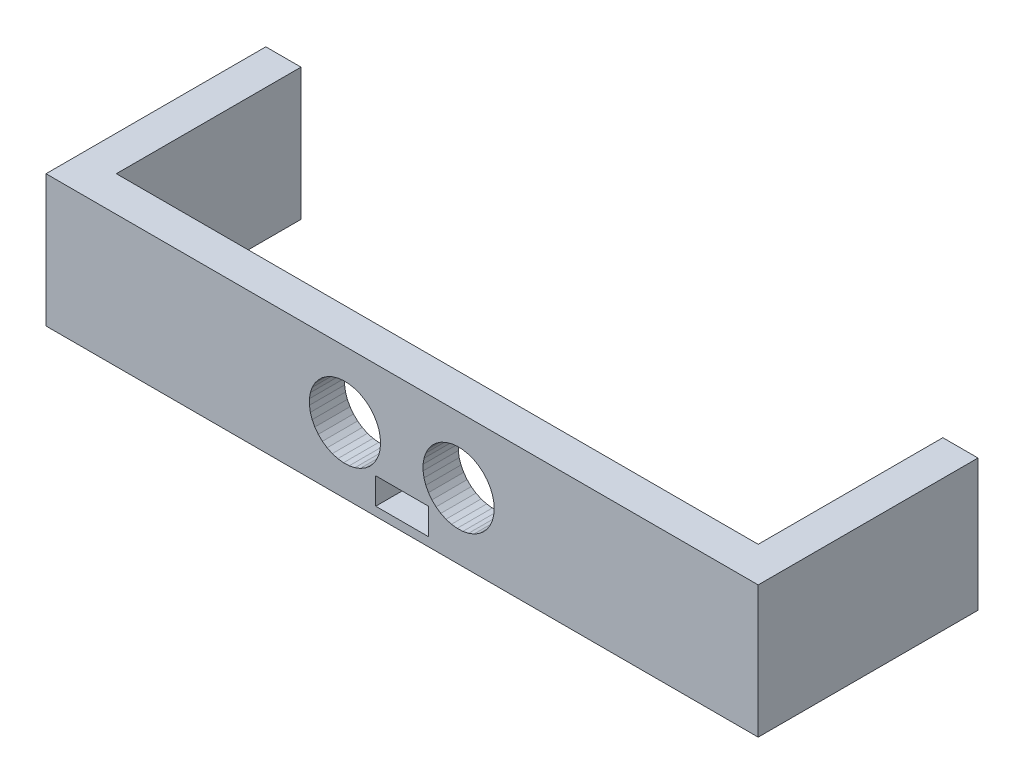
SolidWorks part; units mm, degrees
ref_plane "Front Plane" through (0, 0, 0) normal (0, 0, 1) x (1, 0, 0)
ref_plane "Top Plane" through (0, 0, 0) normal (0, 1, 0) x (1, 0, 0)
ref_plane "Right Plane" through (0, 0, 0) normal (1, 0, 0) x (0, 0, -1)
ref_plane "Plane1" through (0, 30, 0) normal (0, 1, 0) x (1, 0, 0)
sketch "Sketch1" plane through (0, 30, 0) normal (0, 1, 0) x (1, 0, 0)
  line L0 (162, 0) -> (0, 0)
  line L1 (0, 0) -> (0, -50)
  line L2 (0, -50) -> (162, -50)
  line L3 (162, -50) -> (162, 0)
extrude "Boss-Extrude1" add sketch "Sketch1" against normal blind 30
sketch "Sketch2" plane through (0, 0, 0) normal (0, -1, 0) x (1, 0, 0)
  line L0 (8, 0) -> (154, 0)
  line L1 (154, 0) -> (154, 42)
  line L2 (154, 42) -> (8, 42)
  line L3 (8, 42) -> (8, 0)
extrude "Cut-Extrude1" cut sketch "Sketch2" against normal through all
sketch "Sketch3" plane through (0, 0, 50) normal (0, 0, 1) x (1, 0, 0)
  line L0 (85.7763, 14.3482) -> (85.9854, 13.0615)
  line L1 (85.9854, 13.0615) -> (86.3982, 11.8251)
  line L2 (86.3982, 11.8251) -> (87.004, 10.6708)
  line L3 (87.004, 10.6708) -> (87.7871, 9.6287)
  line L4 (87.7871, 9.6287) -> (88.7272, 8.7257)
  line L5 (88.7272, 8.7257) -> (89.8, 7.9852)
  line L6 (89.8, 7.9852) -> (90.9777, 7.4264)
  line L7 (90.9777, 7.4264) -> (92.2298, 7.0637)
  line L8 (92.2298, 7.0637) -> (93.5239, 6.9066)
  line L9 (93.5239, 6.9066) -> (94.8263, 6.9591)
  line L10 (94.8263, 6.9591) -> (96.1036, 7.2198)
  line L11 (96.1036, 7.2198) -> (97.3224, 7.6821)
  line L12 (97.3224, 7.6821) -> (98.4513, 8.3338)
  line L13 (98.4513, 8.3338) -> (99.4611, 9.1583)
  line L14 (99.4611, 9.1583) -> (100.3255, 10.134)
  line L15 (100.3255, 10.134) -> (101.0222, 11.2357)
  line L16 (101.0222, 11.2357) -> (101.5331, 12.435)
  line L17 (101.5331, 12.435) -> (101.8451, 13.7007)
  line L18 (101.8451, 13.7007) -> (101.95, 15)
  line L19 (101.95, 15) -> (101.8451, 16.2993)
  line L20 (101.8451, 16.2993) -> (101.5331, 17.565)
  line L21 (101.5331, 17.565) -> (101.0222, 18.7643)
  line L22 (101.0222, 18.7643) -> (100.3255, 19.866)
  line L23 (100.3255, 19.866) -> (99.4611, 20.8417)
  line L24 (99.4611, 20.8417) -> (98.4513, 21.6662)
  line L25 (98.4513, 21.6662) -> (97.3224, 22.3179)
  line L26 (97.3224, 22.3179) -> (96.1036, 22.7802)
  line L27 (96.1036, 22.7802) -> (94.8263, 23.0409)
  line L28 (94.8263, 23.0409) -> (93.5239, 23.0934)
  line L29 (93.5239, 23.0934) -> (92.2298, 22.9363)
  line L30 (92.2298, 22.9363) -> (90.9777, 22.5736)
  line L31 (90.9777, 22.5736) -> (89.8, 22.0148)
  line L32 (89.8, 22.0148) -> (88.7272, 21.2743)
  line L33 (88.7272, 21.2743) -> (87.7871, 20.3713)
  line L34 (87.7871, 20.3713) -> (87.004, 19.3292)
  line L35 (87.004, 19.3292) -> (86.3982, 18.1749)
  line L36 (86.3982, 18.1749) -> (85.9854, 16.9385)
  line L37 (85.9854, 16.9385) -> (85.7763, 15.6518)
  line L38 (85.7763, 15.6518) -> (85.7763, 14.3482)
extrude "Cut-Extrude2" cut sketch "Sketch3" against normal through all
sketch "Sketch4" plane through (0, 0, 50) normal (0, 0, 1) x (1, 0, 0)
  line L0 (87, 8) -> (75, 8)
  line L1 (75, 8) -> (75, 2)
  line L2 (75, 2) -> (87, 2)
  line L3 (87, 2) -> (87, 8)
extrude "Cut-Extrude3" cut sketch "Sketch4" against normal through all
sketch "Sketch5" plane through (0, 0, 42) normal (0, 0, -1) x (-1, 0, 0)
  line L0 (-70.2536, 22.7802) -> (-71.4724, 22.3179)
  line L1 (-71.4724, 22.3179) -> (-72.6013, 21.6662)
  line L2 (-72.6013, 21.6662) -> (-73.6111, 20.8417)
  line L3 (-73.6111, 20.8417) -> (-74.4755, 19.866)
  line L4 (-74.4755, 19.866) -> (-75.1722, 18.7643)
  line L5 (-75.1722, 18.7643) -> (-75.6831, 17.565)
  line L6 (-75.6831, 17.565) -> (-75.9951, 16.2993)
  line L7 (-75.9951, 16.2993) -> (-76.1, 15)
  line L8 (-76.1, 15) -> (-75.9951, 13.7007)
  line L9 (-75.9951, 13.7007) -> (-75.6831, 12.435)
  line L10 (-75.6831, 12.435) -> (-75.1722, 11.2357)
  line L11 (-75.1722, 11.2357) -> (-74.4755, 10.134)
  line L12 (-74.4755, 10.134) -> (-73.6111, 9.1583)
  line L13 (-73.6111, 9.1583) -> (-72.6013, 8.3338)
  line L14 (-72.6013, 8.3338) -> (-71.4724, 7.6821)
  line L15 (-71.4724, 7.6821) -> (-70.2536, 7.2198)
  line L16 (-70.2536, 7.2198) -> (-68.9764, 6.9591)
  line L17 (-68.9764, 6.9591) -> (-67.6738, 6.9066)
  line L18 (-67.6738, 6.9066) -> (-66.3798, 7.0637)
  line L19 (-66.3798, 7.0637) -> (-65.1277, 7.4264)
  line L20 (-65.1277, 7.4264) -> (-63.95, 7.9852)
  line L21 (-63.95, 7.9852) -> (-62.8772, 8.7257)
  line L22 (-62.8772, 8.7257) -> (-61.9371, 9.6287)
  line L23 (-61.9371, 9.6287) -> (-61.154, 10.6708)
  line L24 (-61.154, 10.6708) -> (-60.5482, 11.8251)
  line L25 (-60.5482, 11.8251) -> (-60.1354, 13.0615)
  line L26 (-60.1354, 13.0615) -> (-59.9263, 14.3482)
  line L27 (-59.9263, 14.3482) -> (-59.9263, 15.6518)
  line L28 (-59.9263, 15.6518) -> (-60.1354, 16.9385)
  line L29 (-60.1354, 16.9385) -> (-60.5482, 18.1749)
  line L30 (-60.5482, 18.1749) -> (-61.154, 19.3292)
  line L31 (-61.154, 19.3292) -> (-61.9371, 20.3713)
  line L32 (-61.9371, 20.3713) -> (-62.8772, 21.2743)
  line L33 (-62.8772, 21.2743) -> (-63.95, 22.0148)
  line L34 (-63.95, 22.0148) -> (-65.1277, 22.5736)
  line L35 (-65.1277, 22.5736) -> (-66.3798, 22.9363)
  line L36 (-66.3798, 22.9363) -> (-67.6738, 23.0934)
  line L37 (-67.6738, 23.0934) -> (-68.9764, 23.0409)
  line L38 (-68.9764, 23.0409) -> (-70.2536, 22.7802)
extrude "Cut-Extrude4" cut sketch "Sketch5" against normal through all
